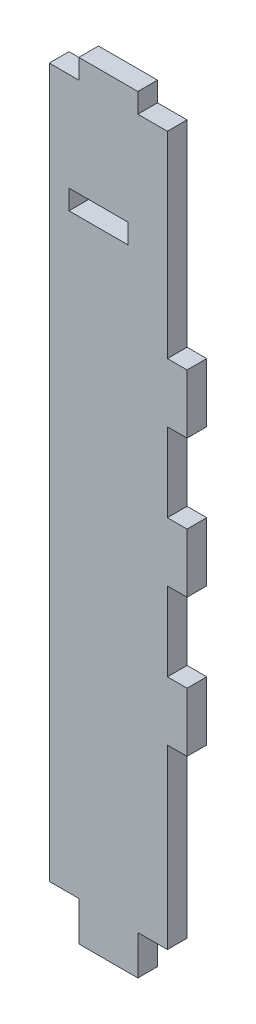
SolidWorks part; units mm, degrees
ref_plane "Front Plane" through (0, 0, 0) normal (0, 0, 1) x (1, 0, 0)
ref_plane "Top Plane" through (0, 0, 0) normal (0, 1, 0) x (1, 0, 0)
ref_plane "Right Plane" through (0, 0, 0) normal (1, 0, 0) x (0, 0, -1)
sketch "Sketch1" plane through (0, 0, 0) normal (0, 0, 1) x (1, 0, 0)
  line L0 (400, 342.5) -> (391.8744, 342.5) construction
  line L1 (430, 435) -> (422.5, 435)
  line L2 (430, 435) -> (430, 385)
  line L3 (430, 255) -> (422.5, 255)
  line L4 (400, 435) -> (400, 255)
  line L5 (407.5, 435) -> (400, 435)
  line L7 (422.5, 435) -> (422.5, 440)
  line L8 (422.5, 440) -> (407.5, 440)
  line L9 (407.5, 435) -> (407.5, 440)
  line L10 (415, 435) -> (407.5, 440) construction
  line L11 (422.5, 440) -> (415, 435) construction
  line L12 (422.5, 245) -> (415, 250) construction
  line L13 (415, 250) -> (407.5, 245) construction
  line L14 (407.5, 255) -> (407.5, 245)
  line L15 (422.5, 245) -> (407.5, 245)
  line L16 (422.5, 255) -> (422.5, 245)
  line L17 (407.5, 255) -> (400, 255)
  line L18 (415, 165) -> (415, 152.4773) construction
  line L19 (430, 335) -> (430, 315)
  line L20 (420, 410) -> (405, 410)
  line L21 (420, 410) -> (420, 405)
  line L22 (420, 405) -> (405, 405)
  line L23 (405, 410) -> (405, 405)
  line L24 (430, 350) -> (435, 350)
  line L26 (430, 335) -> (435, 335)
  line L27 (435, 350) -> (435, 335)
  line L30 (430, 315) -> (435, 315)
  line L31 (435, 315) -> (435, 300)
  line L32 (430, 300) -> (435, 300)
  line L33 (430, 350) -> (435, 350)
  line L34 (435, 350) -> (435, 335)
  line L35 (430, 335) -> (435, 335)
  line L36 (430, 385) -> (435, 385)
  line L37 (435, 385) -> (435, 370)
  line L38 (430, 370) -> (435, 370)
  line L39 (430, 370) -> (430, 350)
  line L40 (430, 300) -> (430, 255)
  point P6 (415, 435)
  point P18 (415, 250)
  point P20 (415, 133.7958)
  point P26 (430, 102.5)
  point P28 (407.5, 255)
  dimension "D1" = 30
  dimension "D2" = 7.5
  dimension "D3" = 15
  dimension "D4" = 5
  dimension "D5" = 5
  dimension "D6" = 10
  dimension "D7" = 15
  dimension "D8" = 25
  dimension "D9" = 15
  dimension "D10" = 5
  dimension "D13" = 97.5
  dimension "D11" = 2
  dimension "D12" = 2
extrude "Boss-Extrude1" add sketch "Sketch1" against normal mid plane 5 contours L40 L32 L31 L30 L19 L26 L27 L24 L39 L38 L37 L36 L2 L1 L7 L8 L9 L5 L4 L17 L14 L15 L16 L3 L23 L20 L21 L22
